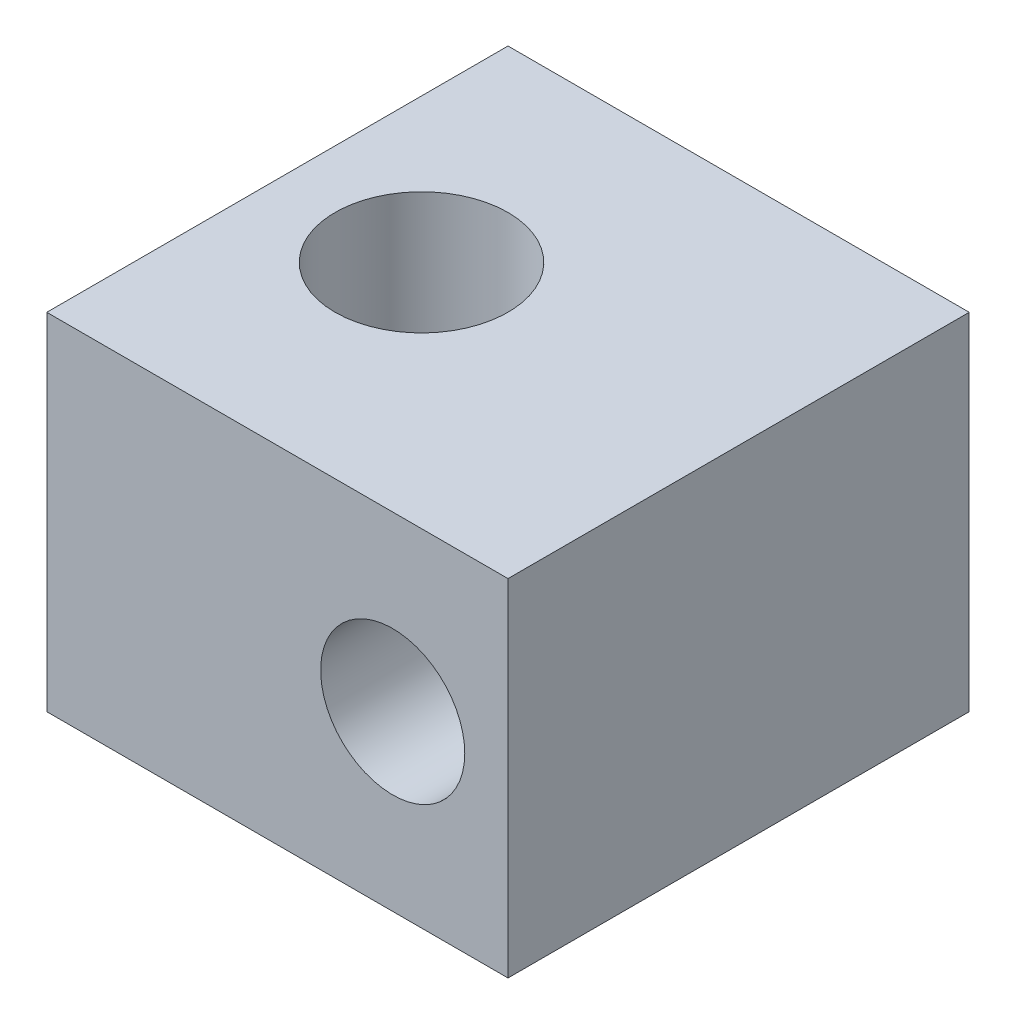
SolidWorks part; units mm, degrees
ref_plane "Přední rovina" through (0, 0, 0) normal (0, 0, 1) x (1, 0, 0)
ref_plane "Horní rovina" through (0, 0, 0) normal (0, 1, 0) x (1, 0, 0)
ref_plane "Pravá rovina" through (0, 0, 0) normal (1, 0, 0) x (0, 0, -1)
sketch "Skica1" plane through (0, 0, 0) normal (0, 1, 0) x (1, 0, 0)
  line L0 (0, 0) -> (-8, 0) construction
  line L1 (8, 8) -> (-8, 8)
  line L2 (8, 8) -> (8, -8)
  line L3 (8, -8) -> (-8, -8)
  line L4 (-8, 8) -> (-8, -8)
  line L5 (8, 8) -> (-8, -8) construction
  line L6 (8, -8) -> (-8, 8) construction
  line L7 (-8, 0) -> (-6, 0) construction
  line L8 (-6, 0) -> (0, 0) construction
  circle A0 centre (-3, 0) radius 3
  point P0 (0, 0)
  dimension "D1" = 16
  dimension "D2" = 16
extrude "Přidat vysunutím1" add sketch "Skica1" along normal blind 12
sketch "Skica2" plane through (0, 0, 8) normal (0, 0, 1) x (1, 0, 0)
  line L0 (8, 6) -> (0, 6) construction
  line L1 (8, 12) -> (8, 0) construction
  line L2 (0, 6) -> (1.5, 6) construction
  line L3 (1.5, 6) -> (4, 6) construction
  circle A0 centre (4, 6) radius 2.5
extrude "Odebrat vysunutím1" cut sketch "Skica2" against normal blind 22
